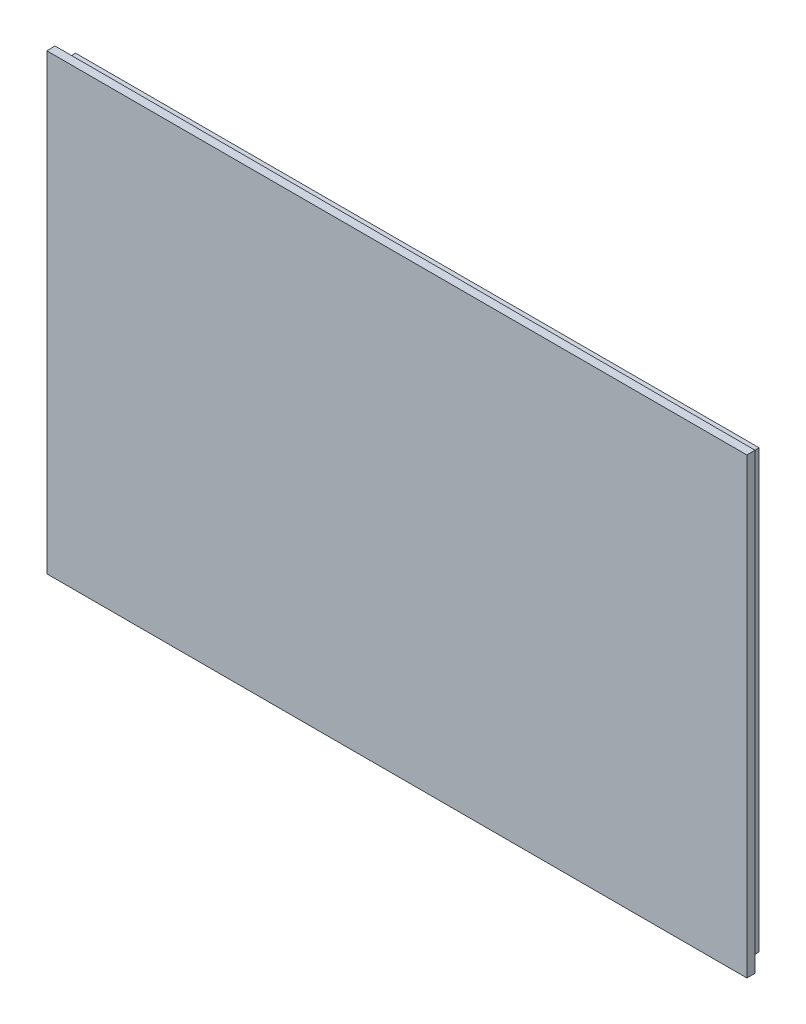
SolidWorks part; units mm, degrees
ref_plane "Front Plane" through (0, 0, 0) normal (0, 0, 1) x (1, 0, 0)
ref_plane "Top Plane" through (0, 0, 0) normal (0, 1, 0) x (1, 0, 0)
ref_plane "Right Plane" through (0, 0, 0) normal (1, 0, 0) x (0, 0, -1)
sketch "Sketch1" plane through (0, 0, 0) normal (0, 0, 1) x (1, 0, 0)
  line L1 (-85, 55) -> (85, 55)
  line L2 (-85, 55) -> (-85, -55)
  line L3 (-85, -55) -> (85, -55)
  line L4 (85, 55) -> (85, -55)
  line L5 (-85, 55) -> (85, -55) construction
  line L6 (-85, -55) -> (85, 55) construction
  point P0 (0, 0)
  dimension "D1" = 170
  dimension "D2" = 110
extrude "Boss-Extrude1" add sketch "Sketch1" along normal blind 2
sketch "Sketch2" plane through (0, 0, 2) normal (0, 0, 1) x (1, 0, 0)
  line L0 (80, -50) -> (80, 50)
  line L1 (80, 50) -> (-80, 50)
  line L2 (-80, 50) -> (-80, -50)
  line L3 (-80, -50) -> (80, -50)
  line L8 (83, -53) -> (83, 53)
  line L9 (83, 53) -> (-83, 53)
  line L10 (-83, 53) -> (-83, -53)
  line L11 (-83, -53) -> (83, -53)
  line L12 (83, -53) -> (83, 53)
  line L13 (83, 53) -> (-83, 53)
  line L14 (-83, 53) -> (-83, -53)
  line L15 (-83, -53) -> (83, -53)
  dimension "D1" = 2
  dimension "D2" = 3
extrude "Boss-Extrude3" add sketch "Sketch2" against normal blind 5
